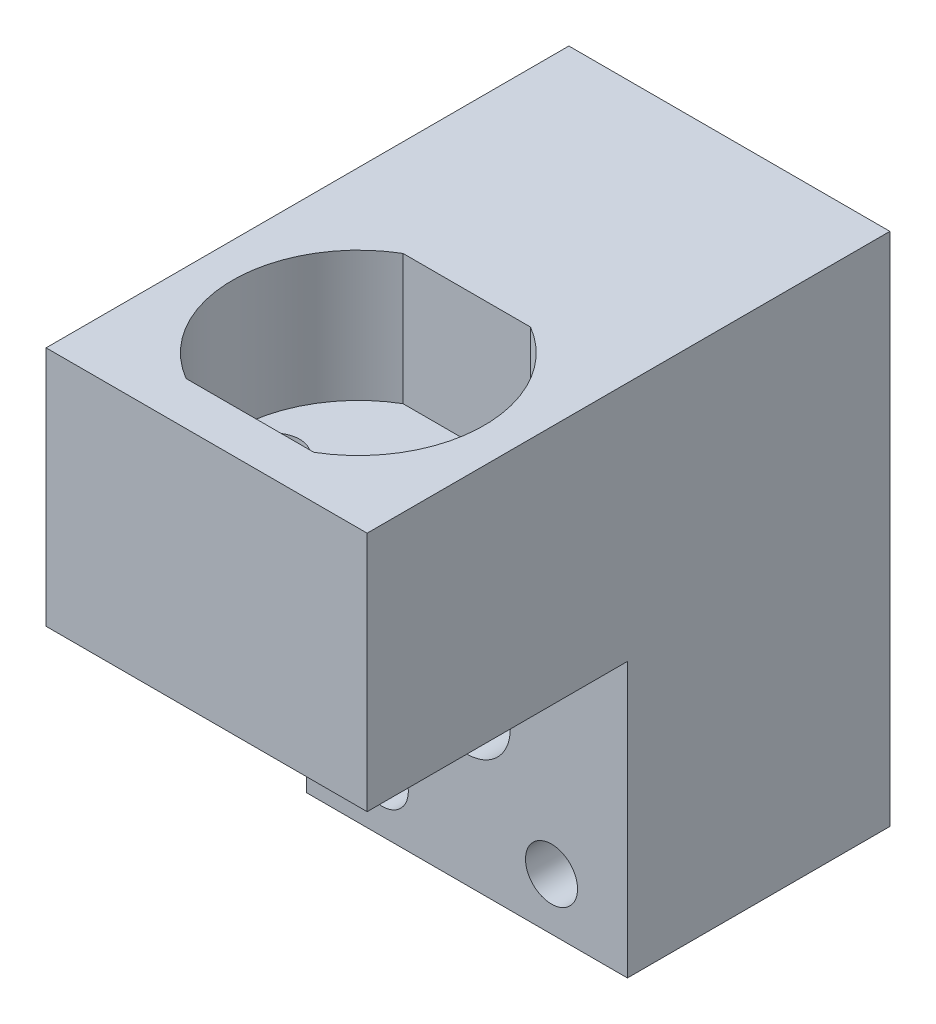
SolidWorks part; units mm, degrees
ref_plane "Спереди" through (0, 0, 0) normal (0, 0, 1) x (1, 0, 0)
ref_plane "Сверху" through (0, 0, 0) normal (0, 1, 0) x (1, 0, 0)
ref_plane "Справа" through (0, 0, 0) normal (1, 0, 0) x (0, 0, -1)
sketch "Эскиз1" plane through (0, 0, 0) normal (0, 0, 1) x (1, 0, 0)
  line L0 (1.9328, 5.37) -> (1.9328, -5.13)
  line L1 (-1.9672, 5.37) -> (-1.9672, -5.13)
  line L2 (-0.6172, 5.16) -> (1.3393, 5.16)
  line L3 (1.3393, 5.16) -> (2.4828, 5.16)
  line L4 (-1.3736, 5.16) -> (-1.0172, 5.16)
  line L5 (-1.3736, 5.16) -> (-2.5172, 5.16)
  line L6 (-2.5172, 5.16) -> (-2.5172, 2.76)
  line L7 (2.4828, 2.76) -> (2.4828, 5.16)
  line L8 (1.3393, 2.76) -> (2.4828, 2.76)
  line L9 (-2.5172, 2.76) -> (-1.3736, 2.76)
  line L10 (1.3393, 2.76) -> (-1.3736, 2.76)
  line L11 (1.6828, 5.37) -> (1.6828, -5.12)
  line L12 (2.1828, -5.12) -> (2.1829, 5.37)
  line L13 (-2.2172, 5.37) -> (-2.2172, -5.12)
  line L14 (-1.7172, -5.12) -> (-1.7171, 5.37)
  line L15 (1.9328, 5.37) -> (1.6828, 5.37)
  line L16 (1.9328, 5.37) -> (2.1829, 5.37)
  line L17 (-1.9672, 5.37) -> (-2.2172, 5.37)
  line L18 (-1.9672, 5.37) -> (-1.7171, 5.37)
  arc A0 (1.9328, -5.37) -> (2.0828, -4.92) centre (1.9328, -5.12) ccw
  arc A1 (1.7828, -4.92) -> (1.9328, -5.37) centre (1.9328, -5.12) ccw
  arc A2 (-2.1172, -4.92) -> (-1.9672, -5.37) centre (-1.9672, -5.12) ccw
  arc A3 (-1.9672, -5.37) -> (-1.8172, -4.92) centre (-1.9672, -5.12) ccw
  arc A4 (2.54, -0.5787) -> (2.8228, -0.1787) centre (2.54, -0.2787) ccw
  arc A5 (2.2572, -0.1787) -> (2.54, -0.5787) centre (2.54, -0.2787) ccw
  arc A6 (0, -0.5787) -> (0.2828, -0.1787) centre (0, -0.2787) ccw
  arc A7 (-0.2828, -0.1787) -> (0, -0.5787) centre (0, -0.2787) ccw
  arc A8 (-2.54, -0.5787) -> (-2.2572, -0.1787) centre (-2.54, -0.2787) ccw
  arc A9 (-2.8228, -0.1787) -> (-2.54, -0.5787) centre (-2.54, -0.2787) ccw
sketch "Эскиз2" plane through (0, 0, 0) normal (0, 0, 1) x (1, 0, 0)
  line L0 (-0.6172, 5.16) -> (1.3393, 5.16) construction
  line L1 (-3.7172, 5.56) -> (3.6828, 5.56)
  line L2 (-3.7172, 5.56) -> (-3.7172, -6.32)
  line L3 (-3.7172, -6.32) -> (3.6828, -6.32)
  line L4 (3.6828, 5.56) -> (3.6828, -6.32)
  line L5 (2.4828, 2.76) -> (2.4828, 5.16) construction
  line L6 (-2.5172, 5.16) -> (-2.5172, 2.76) construction
  circle A0 centre (-1.9672, -5.12) radius 0.6
  circle A1 centre (1.9328, -5.12) radius 0.6
  dimension "D5" = 1.2
  dimension "D1" = 0.4
  dimension "D2" = 1.2
  dimension "D3" = 1.2
  dimension "D4" = 1.2
extrude "Бобышка-Вытянуть1" add sketch "Эскиз2" along normal blind 6.05
sketch "Эскиз3" plane through (0, 0, 6.05) normal (0, 0, 1) x (1, 0, 0)
  line L0 (3.6828, -6.32) -> (3.6828, 5.56) construction
  line L1 (-3.7172, 5.56) -> (3.6828, 5.56)
  line L2 (-3.7172, 5.56) -> (-3.7172, 0)
  line L3 (-3.7172, 0) -> (3.6828, 0)
  line L4 (3.6828, 5.56) -> (3.6828, 0)
extrude "Бобышка-Вытянуть2" add sketch "Эскиз3" along normal blind 5
sketch "Эскиз4" plane through (0, 5.56, 0) normal (0, 1, 0) x (1, 0, 0)
  line L0 (0.9815, -6.4519) -> (1.338, -6.4519)
  line L1 (-1.3749, -6.4519) -> (0.5815, -6.4519)
  line L2 (1.338, -10.6519) -> (-0.6185, -10.6519)
  line L3 (-0.6185, -10.6519) -> (-1.0185, -10.6519)
  line L4 (-1.0185, -10.6519) -> (-1.3749, -10.6519)
  line L5 (0.5815, -6.4519) -> (0.9815, -6.4519)
  line L6 (3.6815, -11.0498) -> (3.6815, 0.0002)
  line L7 (3.6815, -11.0498) -> (-3.7185, -11.0498)
  line L8 (-3.7185, -11.0498) -> (-3.7185, 0.0002)
  line L9 (-3.7185, -6.0498) -> (3.6815, -6.0498)
  arc A0 (1.9315, -8.8019) -> (1.9315, -8.3019) centre (1.9315, -8.5519) ccw
  arc A1 (1.9315, -8.3019) -> (1.9315, -8.8019) centre (1.9315, -8.5519) ccw
  arc A2 (-1.9685, -8.8019) -> (-1.9685, -8.3019) centre (-1.9685, -8.5519) ccw
  arc A3 (-1.9685, -8.3019) -> (-1.9685, -8.8019) centre (-1.9685, -8.5519) ccw
  arc A4 (-1.3749, -6.4519) -> (-1.3749, -10.6519) centre (-0.0185, -8.5519) ccw
  arc A5 (1.338, -10.6519) -> (1.338, -6.4519) centre (-0.0185, -8.5519) ccw
sketch "Эскиз5" plane through (0, 5.56, 0) normal (0, 1, 0) x (1, 0, 0)
  line L0 (-1.0185, -10.6519) -> (-1.3749, -10.6519) construction
  line L1 (-0.6185, -10.6519) -> (-1.0185, -10.6519) construction
  line L2 (1.338, -10.6519) -> (-0.6185, -10.6519) construction
  line L3 (0.9815, -6.4519) -> (1.338, -6.4519) construction
  line L4 (0.5815, -6.4519) -> (0.9815, -6.4519) construction
  line L5 (-1.3749, -6.4519) -> (0.5815, -6.4519) construction
  line L6 (-1.0185, -10.6519) -> (-1.3749, -10.6519)
  line L7 (-0.6185, -10.6519) -> (-1.0185, -10.6519)
  line L8 (1.338, -10.6519) -> (-0.6185, -10.6519)
  line L9 (0.9815, -6.4519) -> (1.338, -6.4519)
  line L10 (0.5815, -6.4519) -> (0.9815, -6.4519)
  line L11 (-1.3749, -6.4519) -> (0.5815, -6.4519)
  arc A0 (1.338, -10.6519) -> (1.338, -6.4519) centre (-0.0185, -8.5519) ccw construction
  arc A1 (-1.3749, -6.4519) -> (-1.3749, -10.6519) centre (-0.0185, -8.5519) ccw construction
  arc A2 (1.338, -10.6519) -> (1.338, -6.4519) centre (-0.0185, -8.5519) ccw
  arc A3 (-1.3749, -6.4519) -> (-1.3749, -10.6519) centre (-0.0185, -8.5519) ccw
extrude "Вырез-Вытянуть1" cut sketch "Эскиз5" against normal blind 3
sketch "Эскиз6" plane through (0, 2.56, 0) normal (0, 1, 0) x (1, 0, 0)
  line L2 (-1.3749, -10.6519) -> (1.338, -10.6519)
  line L3 (1.338, -6.4519) -> (-1.3749, -6.4519)
  line L4 (-1.3749, -10.6519) -> (1.338, -10.6519)
  line L5 (1.338, -6.4519) -> (-1.3749, -6.4519)
  arc A2 (1.338, -10.6519) -> (1.338, -6.4519) centre (-0.0185, -8.5519) ccw
  arc A3 (-1.3749, -6.4519) -> (-1.3749, -10.6519) centre (-0.0185, -8.5519) ccw
  arc A4 (1.338, -10.6519) -> (1.338, -6.4519) centre (-0.0185, -8.5519) ccw
  arc A5 (-1.3749, -6.4519) -> (-1.3749, -10.6519) centre (-0.0185, -8.5519) ccw
  dimension "D1" = 0
extrude "Вырез-Вытянуть-Тонкостенный2" cut sketch "Эскиз6" along normal blind 3 thin
sketch "Эскиз7" plane through (0, 2.56, 0) normal (0, 1, 0) x (1, 0, 0)
  circle A0 centre (-1.9685, -8.5519) radius 0.6
  circle A1 centre (1.9315, -8.5519) radius 0.6
  dimension "D1" = 1.2
extrude "Вырез-Вытянуть2" cut sketch "Эскиз7" against normal through all
sketch "Эскиз8" plane through (0, 0, 0) normal (0, 0, -1) x (-1, 0, 0)
  circle A0 centre (0.0172, -2.7) radius 1
  circle A1 centre (1.9672, -5.12) radius 0.6 construction
  dimension "D1" = 2
  dimension "D2" = 1.95
  dimension "D3" = 2.42
extrude "Вырез-Вытянуть3" cut sketch "Эскиз8" against normal through all
sketch "Эскиз9" plane through (0, 0, 11.05) normal (0, 0, 1) x (1, 0, 0)
  line L1 (-3.7172, 5.56) -> (3.6828, 5.56)
  line L2 (-3.7172, 5.56) -> (-3.7172, 0)
  line L3 (-3.7172, 0) -> (3.6828, 0)
  line L4 (3.6828, 5.56) -> (3.6828, 0)
extrude "Бобышка-Вытянуть3" add sketch "Эскиз9" along normal blind 1
